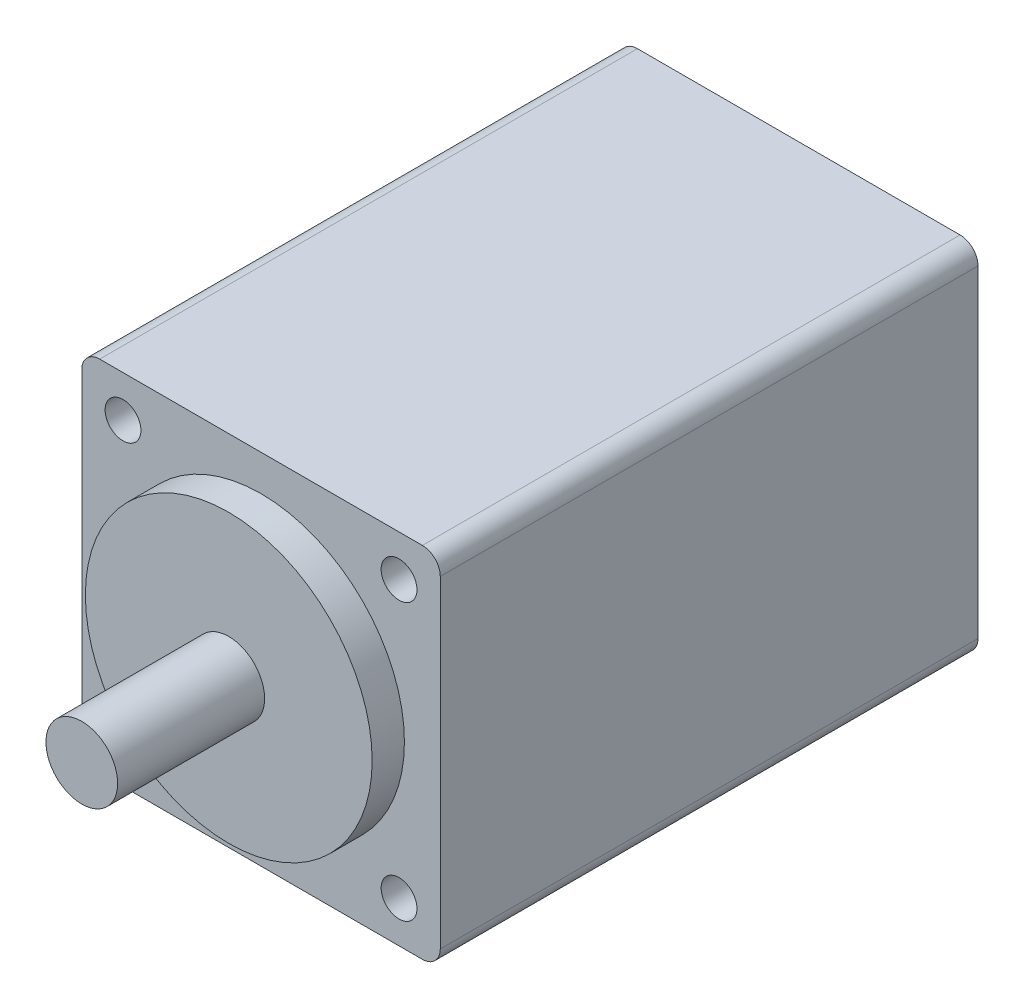
SolidWorks part; units mm, degrees
ref_plane "Front Plane" through (0, 0, 0) normal (0, 0, 1) x (1, 0, 0)
ref_plane "Top Plane" through (0, 0, 0) normal (0, 1, 0) x (1, 0, 0)
ref_plane "Right Plane" through (0, 0, 0) normal (1, 0, 0) x (0, 0, -1)
sketch "Sketch1" plane through (0, 0, 0) normal (0, 0, 1) x (1, 0, 0)
  line L1 (-10, 10) -> (10, 10)
  line L2 (-10, 10) -> (-10, -10)
  line L3 (-10, -10) -> (10, -10)
  line L4 (10, 10) -> (10, -10)
  line L5 (-10, 10) -> (10, -10) construction
  line L6 (-10, -10) -> (10, 10) construction
  point P0 (0, 0)
  dimension "D1" = 20
  dimension "D2" = 20
extrude "Boss-Extrude1" add sketch "Sketch1" along normal blind 30
fillet "Fillet1" radius 1 4 edges at (-10, -10, 15) (-10, 10, 15) (10, -10, 15) (10, 10, 15)
sketch "Sketch2" plane through (0, 0, 30) normal (0, 0, 1) x (1, 0, 0)
  circle A0 centre (0, 0) radius 8
  dimension "D1" = 16
extrude "Boss-Extrude2" add sketch "Sketch2" along normal blind 1.8
sketch "Sketch3" plane through (0, 0, 31.8) normal (0, 0, 1) x (1, 0, 0)
  circle A0 centre (0, 0) radius 2
  dimension "D1" = 4
extrude "Boss-Extrude3" add sketch "Sketch3" along normal blind 8.2
sketch "Sketch4" plane through (0, 0, 30) normal (0, 0, 1) x (1, 0, 0)
  line L0 (-7.7, 7.7) -> (7.7, -7.7) construction
  circle A0 centre (-7.7, 7.7) radius 1
  circle A1 centre (7.7, 7.7) radius 1
  circle A2 centre (7.7, -7.7) radius 1
  circle A3 centre (-7.7, -7.7) radius 1
  point P8 (0, 0)
  point P9 (10.3593, 7.7)
  dimension "D1" = 2
  dimension "D2" = 2
  dimension "D3" = 2
  dimension "D4" = 2
  dimension "D5" = 15.4
  dimension "D6" = 15.4
extrude "Cut-Extrude1" cut sketch "Sketch4" against normal blind 3
